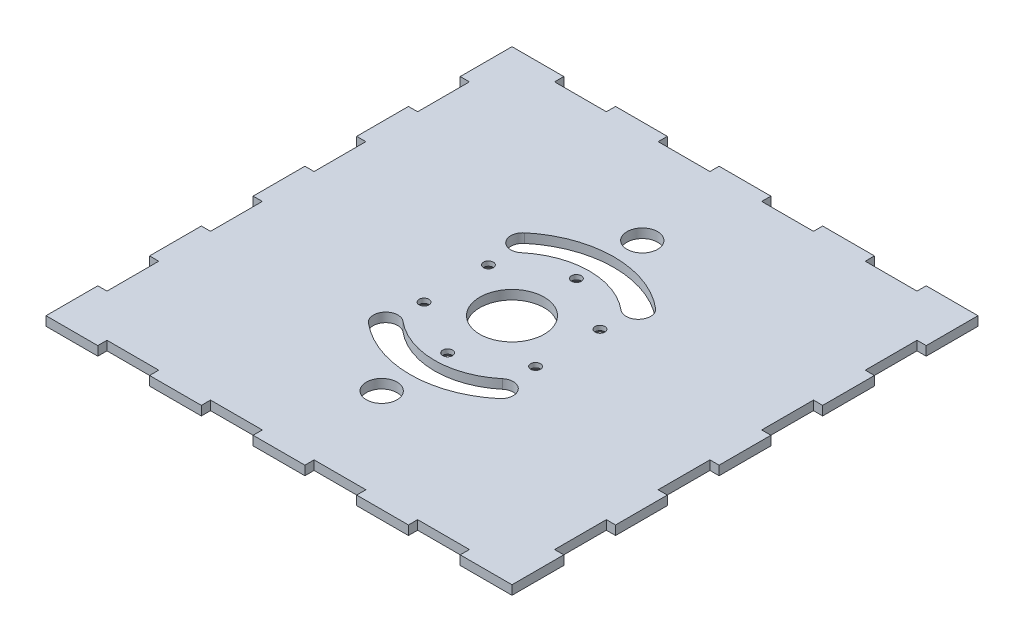
SolidWorks part; units mm, degrees
ref_plane "Front Plane" through (0, 0, 0) normal (0, 0, 1) x (1, 0, 0)
ref_plane "Top Plane" through (0, 0, 0) normal (0, 1, 0) x (1, 0, 0)
ref_plane "Right Plane" through (0, 0, 0) normal (1, 0, 0) x (0, 0, -1)
sketch "Sketch1" plane through (0, 0, 0) normal (0, 1, 0) x (1, 0, 0)
  line L1 (-76, 76) -> (76, 76) construction
  line L2 (-76, 76) -> (-76, -76) construction
  line L3 (-76, -76) -> (76, -76) construction
  line L4 (76, 76) -> (76, -76) construction
  line L5 (0, -76) -> (0, 76) construction
  line L6 (-76, 0) -> (76, 0) construction
  line L8 (-76, -76) -> (-59.1111, -76)
  line L9 (-59.1111, -76) -> (-59.1111, -73)
  line L10 (-59.1111, -73) -> (-42.2222, -73)
  line L11 (-42.2222, -73) -> (-42.2222, -76)
  line L12 (-42.2222, -76) -> (-25.3333, -76)
  line L13 (-25.3333, -76) -> (-25.3333, -73)
  line L14 (-25.3333, -73) -> (-8.4444, -73)
  line L15 (-8.4444, -73) -> (-8.4444, -76)
  line L16 (-8.4444, -76) -> (0, -76)
  line L17 (0, -76) -> (0, -10.5)
  line L18 (-76, -76) -> (-76, -59.1111)
  line L19 (-76, -59.1111) -> (-73, -59.1111)
  line L20 (-73, -59.1111) -> (-73, -42.2222)
  line L21 (-73, -42.2222) -> (-76, -42.2222)
  line L22 (-76, -42.2222) -> (-76, -25.3333)
  line L23 (-76, -25.3333) -> (-73, -25.3333)
  line L24 (-73, -25.3333) -> (-73, -8.4444)
  line L25 (-73, -8.4444) -> (-76, -8.4444)
  line L26 (-76, -8.4444) -> (-76, 0)
  line L27 (-76, 0) -> (-10.5, 0)
  arc A0 (-10.5, 0) -> (0, -10.5) centre (0, 0) ccw
  point P160 (0, 0)
  dimension "D13" = 10.5
  dimension "D2" = 152
  dimension "D3" = 3
  dimension "D4" = 16.8889
  dimension "D5" = 16.8889
  dimension "D6" = 16.8889
  dimension "D7" = 16.8889
  dimension "D8" = 16.8889
  dimension "D9" = 16.8889
  dimension "D10" = 16.8889
  dimension "D11" = 16.8889
  dimension "D12" = 3
extrude "Boss-Extrude1" add sketch "Sketch1" along normal blind 3
mirror "Mirror1" about plane through (0, 0, 0) normal (0, 0, 1) of "Boss-Extrude1"
sketch "Sketch2" plane through (0, 3, 0) normal (0, 1, 0) x (1, 0, 0)
  line L0 (0, 0) -> (0, 21) construction
  circle A0 centre (0, 21) radius 1.6
  dimension "D1" = 3.2
  dimension "D2" = 21
extrude "Cut-Extrude1" cut sketch "Sketch2" against normal through all
chamfer "Chamfer1" distance 1.5 angle 45 1 edges at (0, 0, -19.4)
pattern_circular "CirPattern1" count 6 over 360 about axis through (0, 0, 0) along (0, 1, 0) of "Cut-Extrude1", "Chamfer1"
sketch "Sketch3" plane through (0, 3, 0) normal (0, 1, 0) x (1, 0, 0)
  line L0 (0, 0) -> (0, 29.25) construction
  line L1 (-18.8015, 22.4068) -> (0, 0) construction
  arc A0 (21.6827, 19.6322) -> (-21.6827, 19.6322) centre (0, 0) ccw construction
  arc A1 (-21.3727, 25.471) -> (-16.2304, 19.3426) centre (-18.8015, 22.4068) ccw
  arc A2 (16.2304, 19.3426) -> (21.3727, 25.471) centre (18.8015, 22.4068) ccw
  arc A3 (16.2304, 19.3426) -> (-16.2304, 19.3426) centre (0, 0) ccw
  arc A4 (21.3727, 25.471) -> (-21.3727, 25.471) centre (0, 0) ccw
  circle A5 centre (0, 42.5) radius 5
  dimension "D1" = 4
  dimension "D5" = 10
  dimension "D2" = 40
  dimension "D3" = 29.25
  dimension "D4" = 42.5
extrude "Cut-Extrude2" cut sketch "Sketch3" against normal through all
mirror "Mirror2" about plane through (0, 0, 0) normal (0, 0, 1) of "Cut-Extrude2"
equation "\"D5@Sketch1\"=\"D4@Sketch1\""
equation "\"D6@Sketch1\"=\"D4@Sketch1\""
equation "\"D7@Sketch1\"=\"D4@Sketch1\""
equation "\"D8@Sketch1\"=\"D4@Sketch1\""
equation "\"D9@Sketch1\"=\"D4@Sketch1\""
equation "\"D10@Sketch1\"=\"D4@Sketch1\""
equation "\"D11@Sketch1\"=\"D4@Sketch1\""
equation "\"D12@Sketch1\"=\"D3@Sketch1\""
